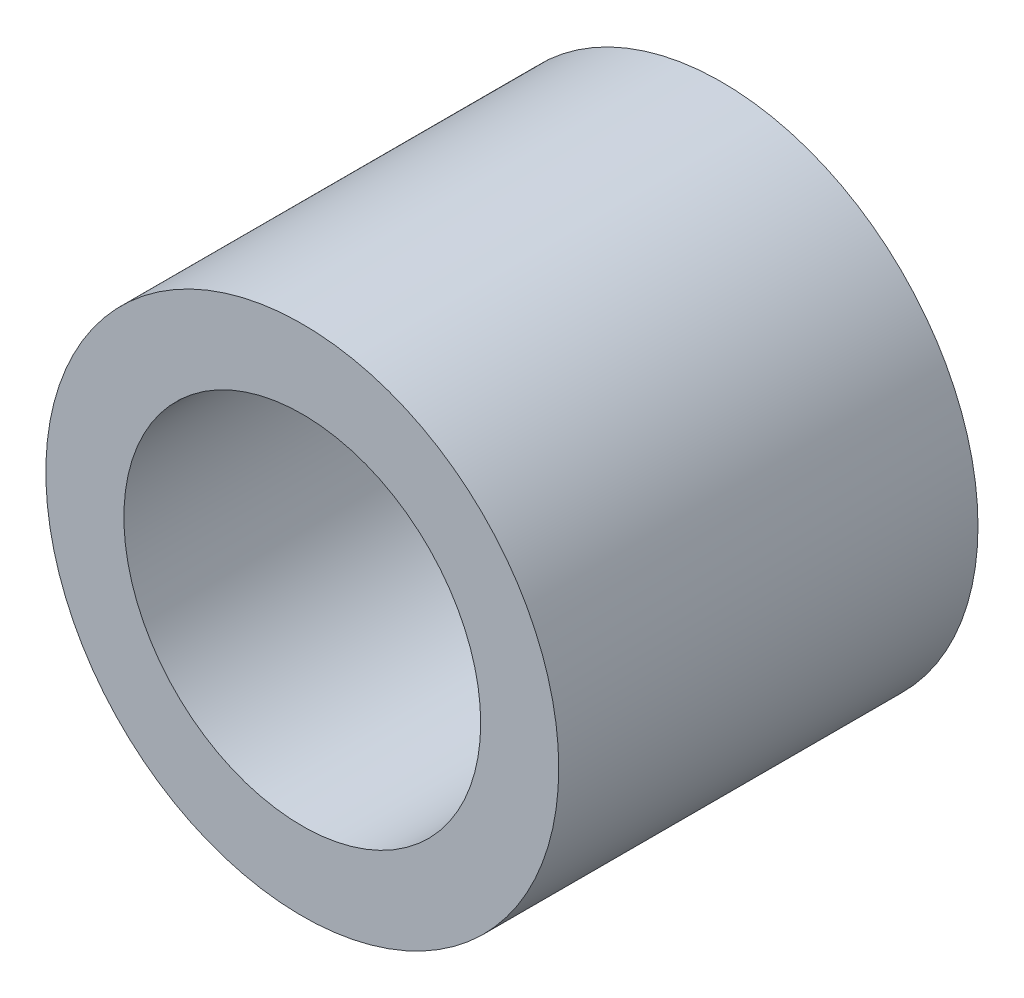
SolidWorks part; units mm, degrees
material "Brass"
ref_plane "Front Plane" through (0, 0, 0) normal (0, 0, 1) x (1, 0, 0)
ref_plane "Top Plane" through (0, 0, 0) normal (0, 1, 0) x (1, 0, 0)
ref_plane "Right Plane" through (0, 0, 0) normal (1, 0, 0) x (0, 0, -1)
sketch "Sketch1" plane through (0, 0, 0) normal (0, 0, 1) x (1, 0, 0)
  circle A0 centre (0, 0) radius 2
  circle A1 centre (0, 0) radius 2.875
  dimension "D1" = 4
  dimension "D2" = 5.75
extrude "Boss-Extrude1" add sketch "Sketch1" along normal blind 4.7
